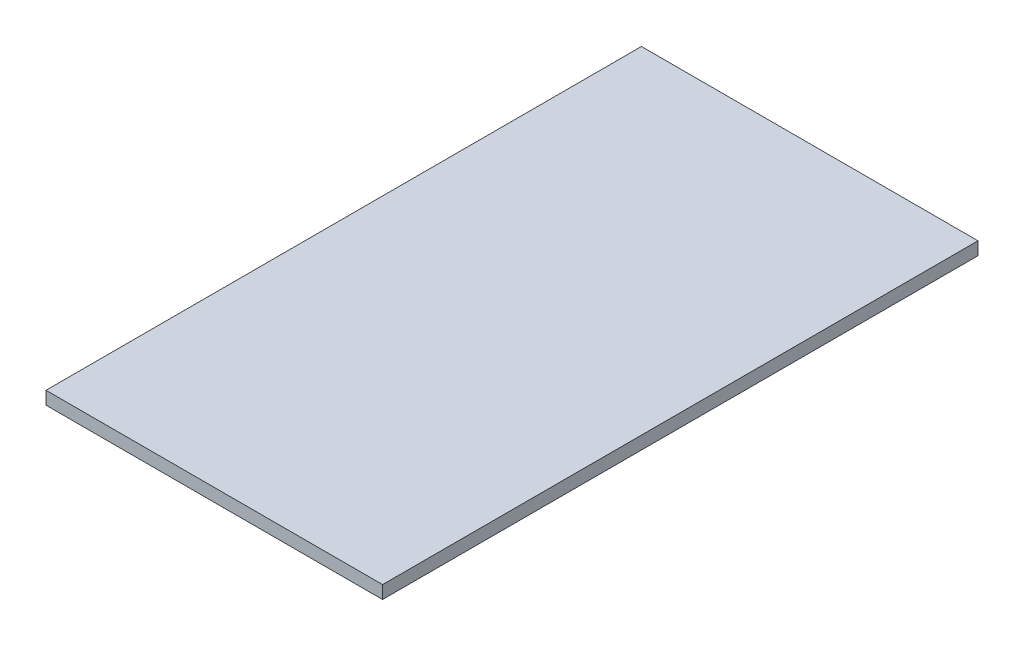
SolidWorks part; units mm, degrees
ref_plane "Front Plane" through (0, 0, 0) normal (0, 0, 1) x (1, 0, 0)
ref_plane "Top Plane" through (0, 0, 0) normal (0, 1, 0) x (1, 0, 0)
ref_plane "Right Plane" through (0, 0, 0) normal (1, 0, 0) x (0, 0, -1)
sketch "Sketch1" plane through (0, 0, 0) normal (0, 1, 0) x (1, 0, 0)
  line L1 (165.1, -292.1) -> (-165.1, -292.1)
  line L2 (165.1, -292.1) -> (165.1, 292.1)
  line L3 (165.1, 292.1) -> (-165.1, 292.1)
  line L4 (-165.1, -292.1) -> (-165.1, 292.1)
  line L5 (165.1, -292.1) -> (-165.1, 292.1) construction
  line L6 (165.1, 292.1) -> (-165.1, -292.1) construction
  point P0 (0, 0)
  dimension "D1" = 584.2
  dimension "D2" = 330.2
extrude "Boss-Extrude1" add sketch "Sketch1" along normal blind 12.7
